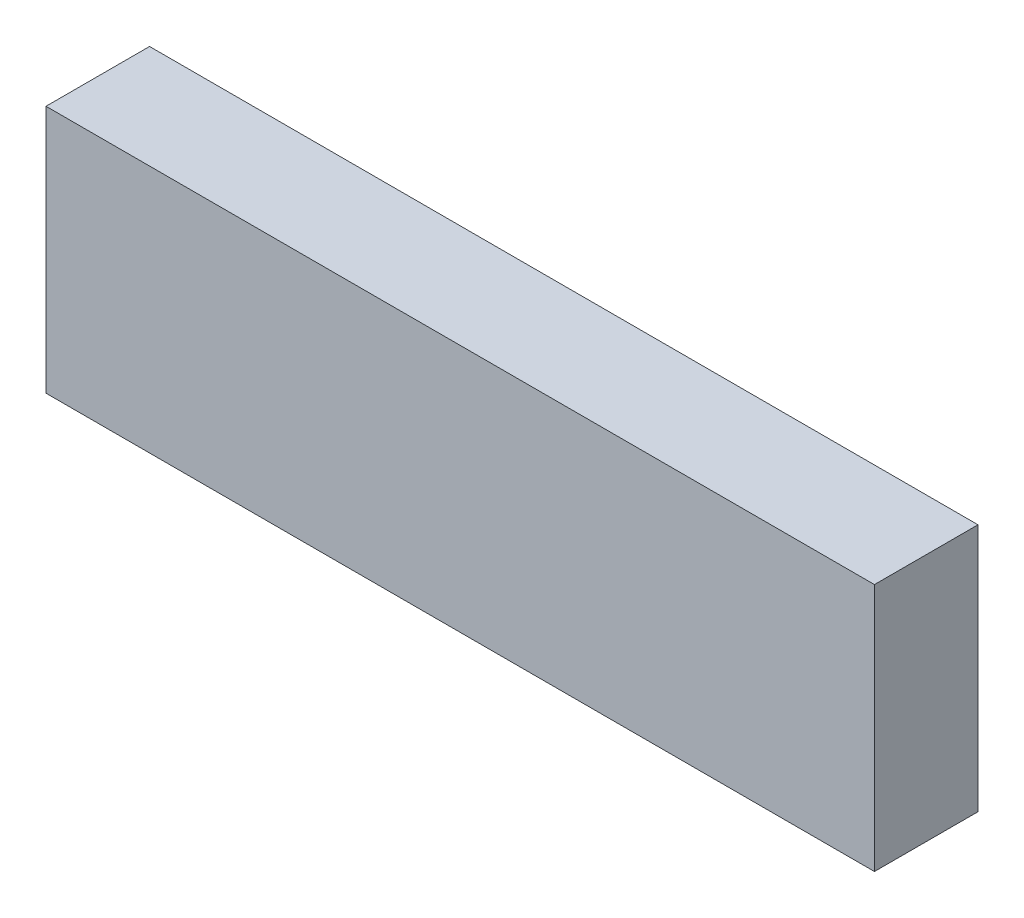
SolidWorks part; units mm, degrees
ref_plane "Plano frontal" through (0, 0, 0) normal (0, 0, 1) x (1, 0, 0)
ref_plane "Plano superior" through (0, 0, 0) normal (0, 1, 0) x (1, 0, 0)
ref_plane "Plano direito" through (0, 0, 0) normal (1, 0, 0) x (0, 0, -1)
sketch "Esboço1" plane through (0, 0, 0) normal (0, 0, 1) x (1, 0, 0)
  line L1 (0, 0) -> (40, 0)
  line L2 (0, 0) -> (0, 12)
  line L3 (0, 12) -> (40, 12)
  line L4 (40, 0) -> (40, 12)
extrude "Ressalto-extrusão1" add sketch "Esboço1" along normal blind 5
